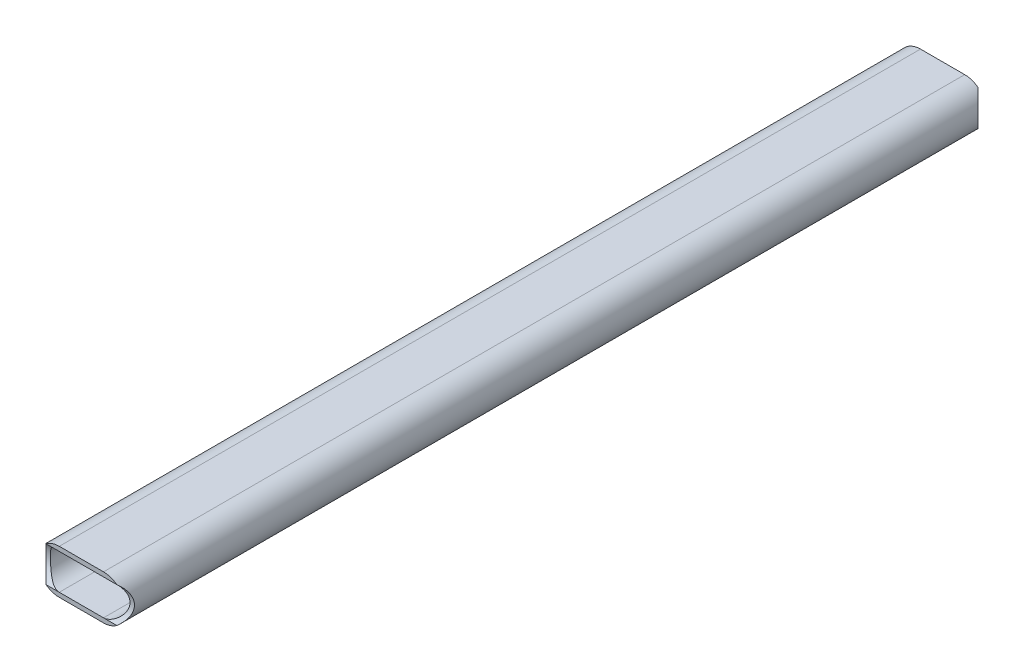
SolidWorks part; units mm, degrees
material "Простая углеродистая сталь"
ref_plane "Спереди" through (0, 0, 0) normal (0, 0, 1) x (1, 0, 0)
ref_plane "Сверху" through (0, 0, 0) normal (0, 1, 0) x (1, 0, 0)
ref_plane "Справа" through (0, 0, 0) normal (1, 0, 0) x (0, 0, -1)
sketch "Эскиз1" plane through (0, 0, 0) normal (0, 0, 1) x (1, 0, 0)
  line L0 (0, 0) -> (15, 0) construction
  line L1 (0, 7.5) -> (15, 7.5)
  line L2 (0, -7.5) -> (15, -7.5)
  line L3 (0, 6) -> (15, 6)
  line L4 (0, -6) -> (15, -6)
  arc A0 (0, 7.5) -> (0, -7.5) centre (0, 0) ccw
  arc A1 (15, -7.5) -> (15, 7.5) centre (15, 0) ccw
  arc A2 (15, -6) -> (15, 6) centre (15, 0) ccw
  arc A3 (0, 6) -> (0, -6) centre (0, 0) ccw
  point P3 (7.5, 0)
  dimension "D1" = 15
  dimension "D2" = 30
  dimension "D3" = 1.5
extrude "Бобышка-Вытянуть1" add sketch "Эскиз1" along normal blind 292
sketch "Эскиз2" plane through (0, 0, 0) normal (1, 0, 0) x (0, 0, -1)
  line L0 (0, -7.5) -> (0, 7.5) construction
  line L2 (-292, 7.5) -> (-292, -7.5) construction
  circle A0 centre (4.5, 0) radius 7.5
  circle A1 centre (-296.5, 0) radius 7.5
  dimension "D1" = 15
  dimension "D3" = 3
  dimension "D2" = 3
extrude "Вырез-Вытянуть1" cut sketch "Эскиз2" against normal through all and the other way through all
